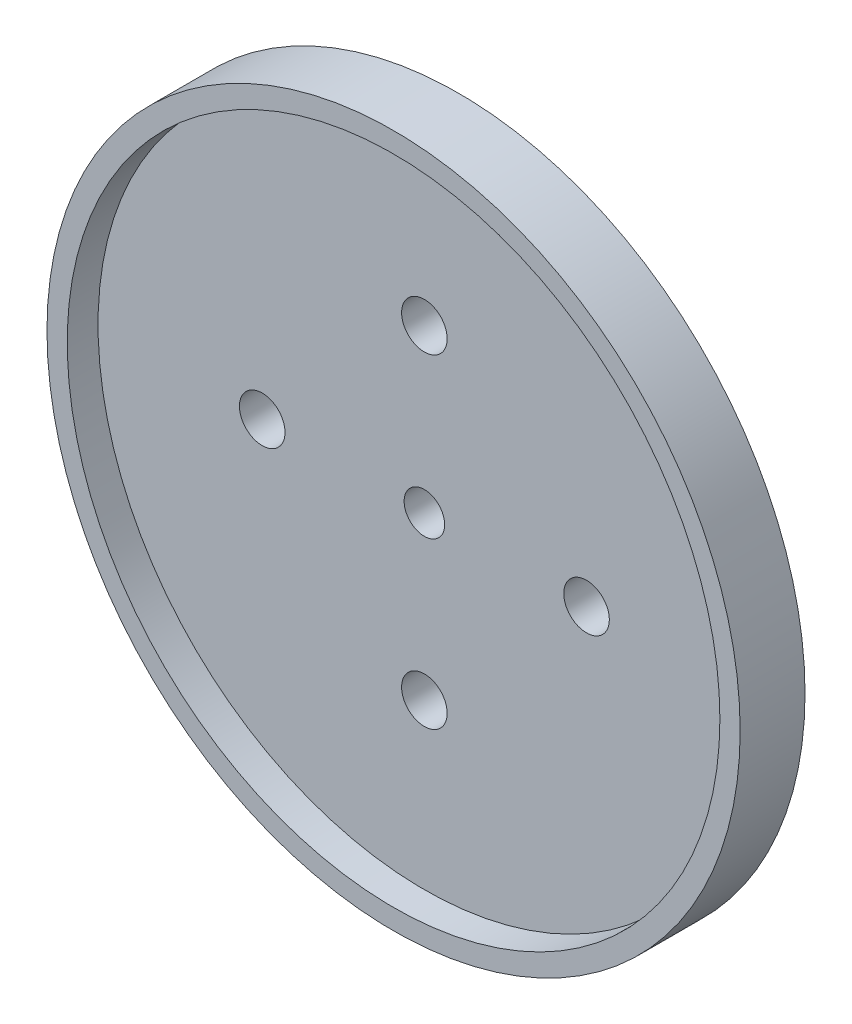
SolidWorks part; units mm, degrees
ref_plane "Front Plane" through (0, 0, 0) normal (0, 0, 1) x (1, 0, 0)
ref_plane "Top Plane" through (0, 0, 0) normal (0, 1, 0) x (1, 0, 0)
ref_plane "Right Plane" through (0, 0, 0) normal (1, 0, 0) x (0, 0, -1)
sketch "Sketch1" plane through (0, 0, 0) normal (0, 0, 1) x (1, 0, 0)
  circle A0 centre (0, 0) radius 54.2925
  dimension "D1" = 108.585
extrude "Extrude1" add sketch "Sketch1" along normal blind 10.16
sketch "Sketch2" plane through (0, 0, 10.16) normal (0, 0, 1) x (1, 0, 0)
  circle A0 centre (0, 0) radius 51.1175
  circle A1 centre (0, 0) radius 54.2925 construction
  dimension "D1" = 3.175
extrude "Extrude2" cut sketch "Sketch2" against normal blind 4.826
hole_wizard "1/4 (0.25) Diameter Hole1" positions "Sketch4" profile "Sketch3" hole size "1/4" standard "Ansi Inch"
sketch "Sketch4" plane through (0, 0, 5.334) normal (0, 0, 1) x (1, 0, 0)
  point P1 (0, 0)
sketch "Sketch3" plane through (0, 0, 5.334) normal (1, 0, 0) x (0, -1, 0)
  line L0 (0, 0) -> (0, 8.2577)
  line L1 (0, 8.2577) -> (3.175, 6.35)
  line L2 (3.175, 6.35) -> (3.175, 0)
  line L5 (3.175, 0) -> (0, 0)
  line L10 (0, 8.2577) -> (-3.175, 6.35) construction
  line L11 (0, -6.35) -> (0, 107.95) construction
  dimension "Hole Dia." = 6.35
  dimension "Hole Depth" = 6.35
  dimension "Drill Angle" = 118
sketch "Sketch5" plane through (0, 0, 5.334) normal (0, 0, 1) x (1, 0, 0)
  line L0 (0, 0) -> (25.4, 0) construction
  dimension "D1" = 25.4
hole_wizard "1/4 Clearance Hole1" positions "3DSketch1" profile "Sketch6" hole size "1/4" standard "Ansi Inch" end condition through all
sketch3d "3DSketch1"
  point P0 (25.4, 0, 5.334)
sketch "Sketch6" plane through (25.4, 0, 5.334) normal (1, 0, 0) x (0, -1, 0)
  line L0 (0, 0) -> (0, 5.334)
  line L1 (0, 5.334) -> (3.5712, 5.334)
  line L2 (3.5712, 5.334) -> (3.5712, 0)
  line L5 (3.5712, 0) -> (0, 0)
  line L11 (0, -6.35) -> (0, 107.95) construction
  dimension "Thru Hole Dia." = 7.1425
  dimension "Thru Hole Depth" = 5.334
pattern_circular "CirPattern1" count 4 over 360 about axis through (0, 0, 0) along (0, 0, 1) of "1/4 Clearance Hole1"
